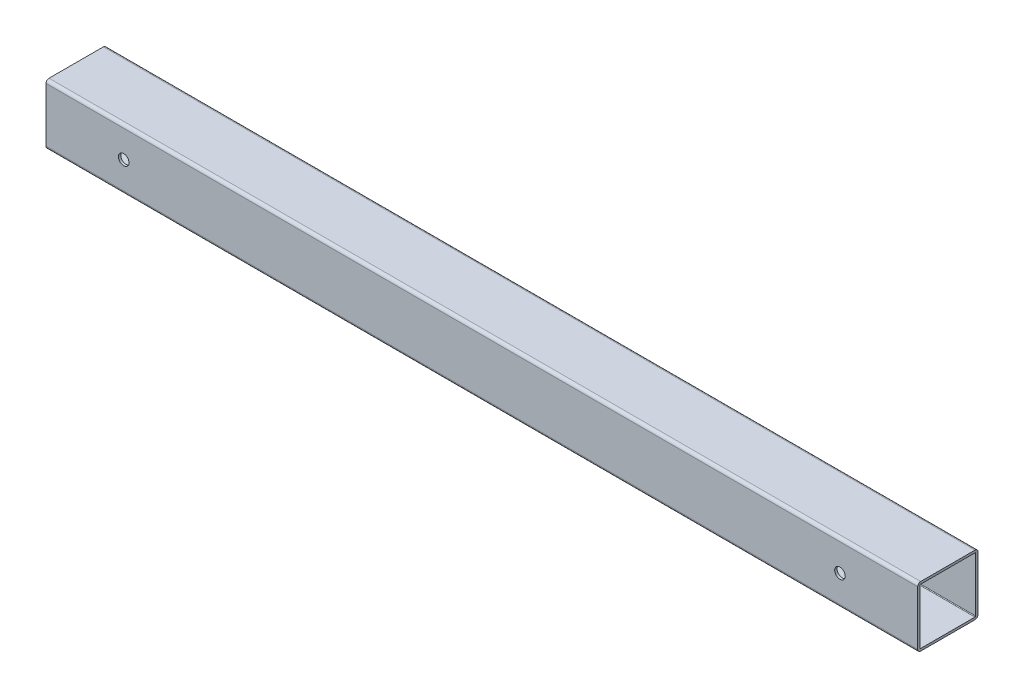
SolidWorks part; units mm, degrees
material "AISI 1020"
material "AISI 1020"
material "AISI 1020"
ref_plane "Plano frontal" through (0, 0, 0) normal (0, 0, 1) x (1, 0, 0)
ref_plane "Plano superior" through (0, 0, 0) normal (0, 1, 0) x (1, 0, 0)
ref_plane "Plano direito" through (0, 0, 0) normal (1, 0, 0) x (0, 0, -1)
other "Caixa delimitadora"
ref_plane "Default Plane" through (-289.0268, -20, -20) normal (0, 1, 0) x (1, 0, 0)
sketch "Esboço3" plane through (0, 0, 0) normal (0, 0, 1) x (1, 0, 0)
  line L0 (-289.0268, 0) -> (289.0268, 0)
  line L1 (-289.0268, -515.7728) -> (289.0268, -515.7728)
  point P6 (0, 0)
other " C:\\USERS\\RAULSTAR\\MEU DRIVE\\TEMPLATES\\BIBLIOTECA SOLDAGEM SOLIDWORKS\\METALON\\QUADRADO\\40 X 40 X 1,55 - ESTÁ FALTANDO(1)"
ref_plane "Plano1" through (-289.0268, 0, 0) normal (1, 0, 0) x (0, 1, 0)
sketch "Esboço1" plane through (-289.0268, 0, 0) normal (1, 0, 0) x (0, 1, 0)
  line L0 (-18, -18.45) -> (18, -18.45)
  line L1 (-18.45, -18) -> (-18.45, 18)
  line L2 (18, 18.45) -> (-18, 18.45)
  line L3 (18.45, 18) -> (18.45, -18)
  line L4 (-18, -20) -> (18, -20)
  line L5 (-20, -18) -> (-20, 18)
  line L6 (18, 20) -> (-18, 20)
  line L7 (20, 18) -> (20, -18)
  line L8 (-20, 0) -> (-18.45, 0) construction
  line L9 (-18.45, 0) -> (18.45, 0) construction
  line L10 (18.45, 0) -> (20, 0) construction
  line L11 (0, 20) -> (0, 18.45) construction
  line L12 (0, 18.45) -> (0, -18.45) construction
  line L13 (0, -18.45) -> (0, -20) construction
  arc A0 (20, 18) -> (18, 20) centre (18, 18) ccw
  arc A1 (18, -20) -> (20, -18) centre (18, -18) ccw
  arc A2 (-20, -18) -> (-18, -20) centre (-18, -18) ccw
  arc A3 (-18, 20) -> (-20, 18) centre (-18, 18) ccw
  arc A4 (-18, 18.45) -> (-18.45, 18) centre (-18, 18) ccw
  arc A5 (18.45, 18) -> (18, 18.45) centre (18, 18) ccw
  arc A6 (18, -18.45) -> (18.45, -18) centre (18, -18) ccw
  arc A7 (-18.45, -18) -> (-18, -18.45) centre (-18, -18) ccw
  point P32 (0, 0)
  point P33 (0, 0)
  dimension "D1" = 2
  dimension "D2" = 40
  dimension "D3" = 40
  dimension "D4" = 1.55
sketch "Esboço4" plane through (0, 0, -20) normal (0, 0, -1) x (-1, 0, 0)
  line L0 (289.0268, 0) -> (-289.0268, 0) construction
  line L1 (0, 0) -> (0, -20) construction
  line L2 (-289.0268, -20) -> (289.0268, -20) construction
  line L3 (289.0268, -515.7728) -> (-289.0268, -515.7728) construction
  line L5 (289.0268, -18) -> (289.0268, 18) construction
  circle A0 centre (-237.5, 0) radius 3.5
  circle A1 centre (237.5, 0) radius 3.5
  circle A2 centre (-237.5, -515.7728) radius 3.5
  circle A3 centre (237.5, -515.7728) radius 3.5
  dimension "D1" = 7
  dimension "D2" = 51.5268
extrude "Corte-extrusão1" cut sketch "Esboço4" against normal through all both and the other way through all
equation "\"D3@Esboço1\"=\"D2@Esboço1\""
